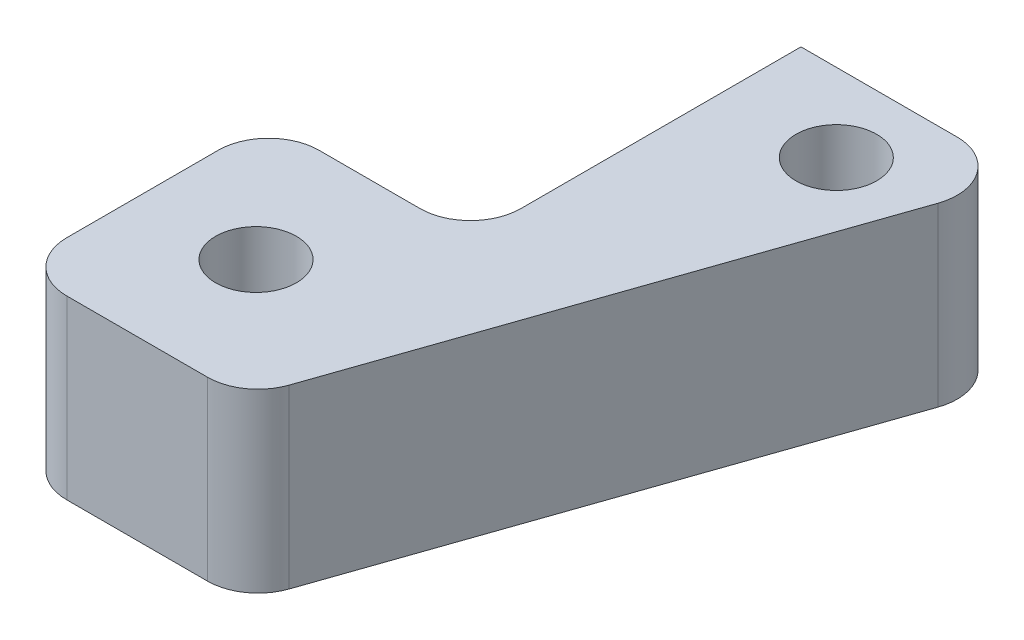
SolidWorks part; units mm, degrees
ref_plane "Front" through (0, 0, 0) normal (0, 0, 1) x (1, 0, 0)
ref_plane "Top" through (0, 0, 0) normal (0, 1, 0) x (1, 0, 0)
ref_plane "Right" through (0, 0, 0) normal (1, 0, 0) x (0, 0, -1)
ref_plane "Plane1" through (0, -35.7488, 0) normal (0, 1, 0) x (1, 0, 0)
sketch "Sketch2" plane through (0, -35.7488, 0) normal (0, 1, 0) x (1, 0, 0)
  line L0 (-37.2033, -43.48) -> (-37.2033, -28.48) construction
  line L1 (-29.2033, -28.48) -> (-37.2033, -28.48) construction
  line L2 (-41.7033, -48.48) -> (-32.7033, -48.48)
  line L4 (-40.7033, -38.48) -> (-33.7033, -38.48)
  line L6 (-32.7033, -48.48) -> (-41.7033, -48.48)
  line L11 (-41.7033, -48.48) -> (-41.7033, -38.48)
  line L12 (-33.7033, -38.48) -> (-41.7033, -38.48)
  line L13 (-32.7033, -48.48) -> (-24.7033, -25.3802)
  line L14 (-33.7033, -25.3802) -> (-33.7033, -38.48)
  line L15 (-33.7033, -25.3802) -> (-24.7033, -25.3802)
  circle A1 centre (-37.2033, -43.48) radius 1.6
  circle A2 centre (-29.2033, -28.48) radius 1.6
  point P10 (-37.2033, -48.48)
  dimension "D2" = 3.2
  dimension "D4" = 9
extrude "Boss-Extrude1" add sketch "Sketch2" along normal blind 7 contours L15 L14 L4 L12 L11 L2 L13 A1 A2
fillet "Fillet1" radius 2 1 edges at (-24.7033, -32.2488, 25.3802)
fillet "Fillet2" radius 2 4 edges at (-32.7033, -32.2488, 48.48) (-41.7033, -32.2488, 48.48) (-41.7033, -32.2488, 38.48) (-33.7033, -32.2488, 38.48)
